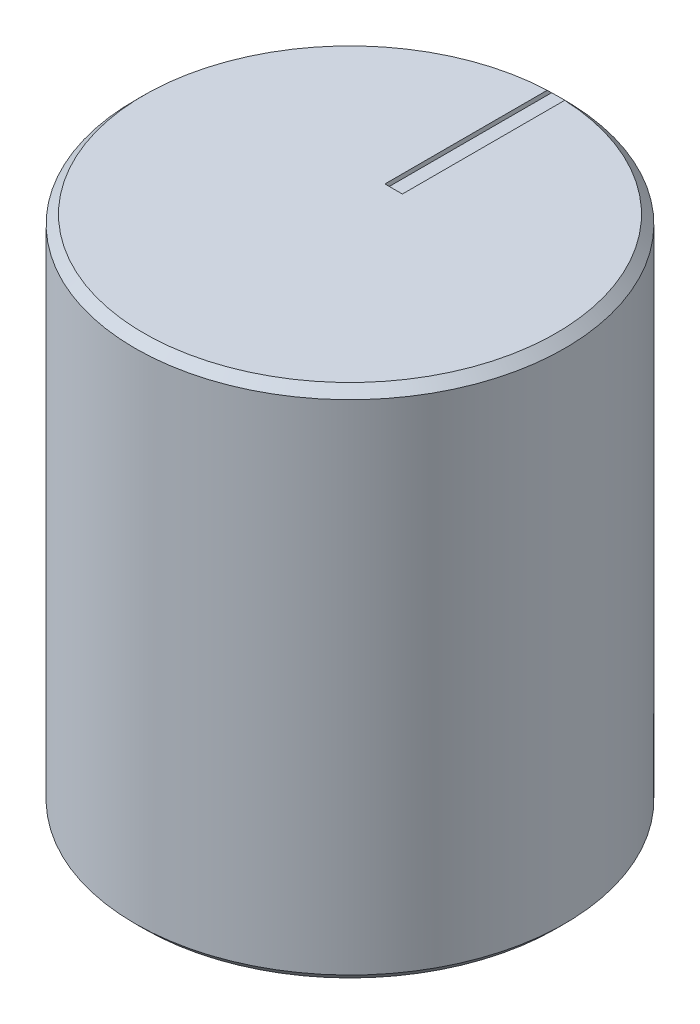
SolidWorks part; units mm, degrees
ref_plane "Front Plane" through (0, 0, 0) normal (0, 0, 1) x (1, 0, 0)
ref_plane "Top Plane" through (0, 0, 0) normal (0, 1, 0) x (1, 0, 0)
ref_plane "Right Plane" through (0, 0, 0) normal (1, 0, 0) x (0, 0, -1)
sketch "Sketch1" plane through (0, 0, 0) normal (0, 1, 0) x (1, 0, 0)
  circle A0 centre (0, 0) radius 6.25
  dimension "D1" = 12.5
extrude "Boss-Extrude1" add sketch "Sketch1" along normal blind 15
chamfer "Chamfer1" distance 0.254 angle 45 2 edges at (0, 15, 6.25) (0, 0, 6.25)
sketch "Sketch2" plane through (0, 15, 0) normal (0, 1, 0) x (1, 0, 0)
  line L1 (-0.254, 6.2138) -> (0.254, 6.2138)
  line L2 (-0.254, 6.2138) -> (-0.254, 1.27)
  line L3 (-0.254, 1.27) -> (0.254, 1.27)
  line L4 (0.254, 6.2138) -> (0.254, 1.27)
  point P4 (0, 0)
  point P5 (0, 1.27)
  dimension "D1" = 0.508
  dimension "D2" = 1.27
extrude "Cut-Extrude1" cut sketch "Sketch2" against normal blind 0.127
